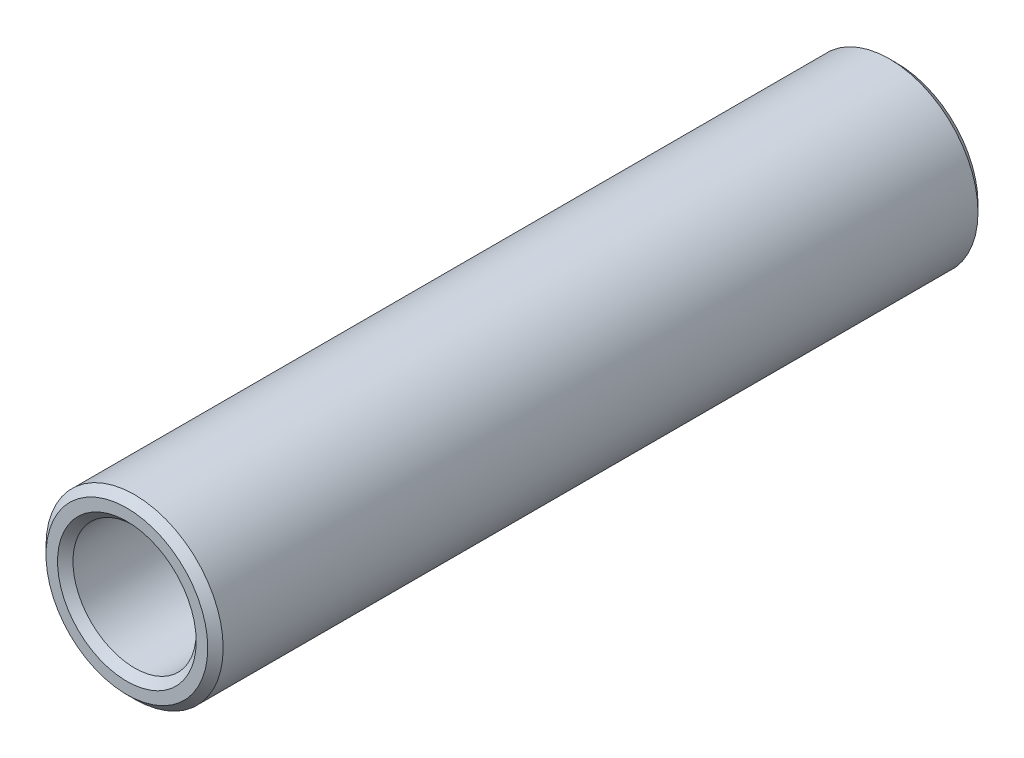
SolidWorks part; units mm, degrees
ref_plane "前视基准面" through (0, 0, 0) normal (0, 0, 1) x (1, 0, 0)
ref_plane "上视基准面" through (0, 0, 0) normal (0, 1, 0) x (1, 0, 0)
ref_plane "右视基准面" through (0, 0, 0) normal (1, 0, 0) x (0, 0, -1)
sketch "草图1" plane through (0, 0, 0) normal (0, 0, 1) x (1, 0, 0)
  circle A0 centre (0, 0) radius 11.5
  circle A1 centre (0, 0) radius 8
  dimension "D1" = 23
  dimension "D2" = 16
extrude "凸台-拉伸1" add sketch "草图1" along normal blind 100
chamfer "倒角1" distance 1 angle 45 4 edges at (8, 0, 0) (8, 0, 100) (11.5, 0, 0) (11.5, 0, 100)
